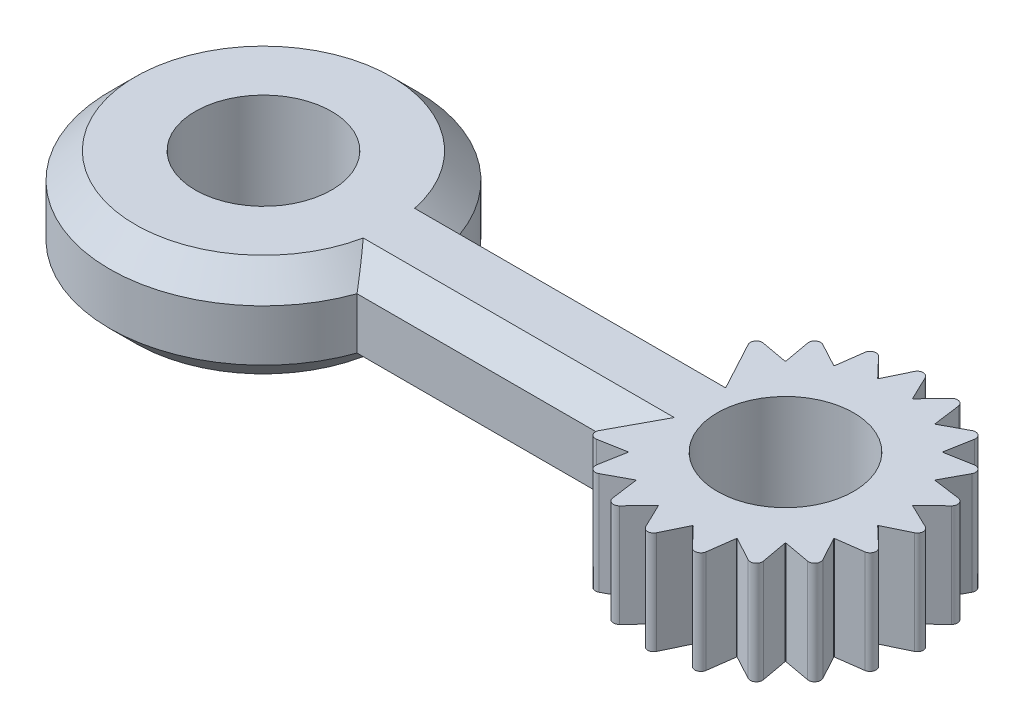
SolidWorks part; units mm, degrees
ref_plane "Front Plane" through (0, 0, 0) normal (0, 0, 1) x (1, 0, 0)
ref_plane "Top Plane" through (0, 0, 0) normal (0, 1, 0) x (1, 0, 0)
ref_plane "Right Plane" through (0, 0, 0) normal (1, 0, 0) x (0, 0, -1)
sketch "Sketch1" plane through (0, 0, 0) normal (0, 1, 0) x (1, 0, 0)
  line L0 (-21.5, 0) -> (-6.5, 0) construction
  line L1 (-22.0159, 3) -> (-5.7663, 3)
  line L2 (-22.0159, -3) -> (-5.7663, -3)
  line L3 (0, 6.5) -> (0, 8.5) construction
  line L4 (0, 8.5) -> (1, 6.4226)
  line L5 (0, 8.5) -> (-1, 6.4226)
  line L6 (2.6266, 8.084) -> (2.9358, 5.7993)
  line L7 (2.6266, 8.084) -> (1.0336, 6.4173)
  line L8 (4.9962, 6.8766) -> (4.5841, 4.6082)
  line L9 (4.9962, 6.8766) -> (2.9661, 5.7838)
  line L10 (6.8766, 4.9962) -> (5.7838, 2.9661)
  line L11 (6.8766, 4.9962) -> (4.6082, 4.5841)
  line L12 (8.084, 2.6266) -> (6.4173, 1.0336)
  line L13 (8.084, 2.6266) -> (5.7993, 2.9358)
  line L14 (8.5, 0) -> (6.4226, -1)
  line L15 (8.5, 0) -> (6.4226, 1)
  line L16 (8.084, -2.6266) -> (5.7993, -2.9358)
  line L17 (8.084, -2.6266) -> (6.4173, -1.0336)
  line L18 (6.8766, -4.9962) -> (4.6082, -4.5841)
  line L19 (6.8766, -4.9962) -> (5.7838, -2.9661)
  line L20 (4.9962, -6.8766) -> (2.9661, -5.7838)
  line L21 (4.9962, -6.8766) -> (4.5841, -4.6082)
  line L22 (2.6266, -8.084) -> (1.0336, -6.4173)
  line L23 (2.6266, -8.084) -> (2.9358, -5.7993)
  line L24 (0, -8.5) -> (-1, -6.4226)
  line L25 (0, -8.5) -> (1, -6.4226)
  line L26 (-2.6266, -8.084) -> (-2.9358, -5.7993)
  line L27 (-2.6266, -8.084) -> (-1.0336, -6.4173)
  line L28 (-4.9962, -6.8766) -> (-4.5841, -4.6082)
  line L29 (-4.9962, -6.8766) -> (-2.9661, -5.7838)
  line L30 (-6.8766, -4.9962) -> (-5.7838, -2.9661)
  line L31 (-6.8766, -4.9962) -> (-4.6082, -4.5841)
  line L32 (-5.802, 3) -> (-5.7838, 2.9661)
  line L39 (-6.8766, 4.9962) -> (-4.6082, 4.5841)
  line L40 (-6.8766, 4.9962) -> (-5.7838, 2.9661)
  line L41 (-4.9962, 6.8766) -> (-2.9661, 5.7838)
  line L42 (-8.084, -2.6266) -> (-6.4173, -1.0336) [skipped]
  line L43 (-8.084, -2.6266) -> (-5.7993, -2.9358) [skipped]
  line L44 (-6.8766, -4.9962) -> (-5.7838, -2.9661) [skipped]
  line L45 (-6.8766, -4.9962) -> (-4.6082, -4.5841) [skipped]
  line L46 (-8.5, 0) -> (-14.7322, 3) [skipped]
  line L47 (-8.5, 0) -> (-6.4226, 1) [skipped]
  line L48 (-8.084, 2.6266) -> (-6.4173, 1.0336) [skipped]
  line L49 (-8.084, 2.6266) -> (-5.7993, 2.9358) [skipped]
  line L50 (-6.8766, 4.9962) -> (-4.6082, 4.5841) [skipped]
  line L51 (-4.9962, 6.8766) -> (-4.5841, 4.6082) [skipped]
  line L52 (-4.9962, 6.8766) -> (-2.9661, 5.7838) [skipped]
  line L53 (-2.6266, 8.084) -> (-2.9358, 5.7993) [skipped]
  line L54 (-2.6266, 8.084) -> (-1.0336, 6.4173) [skipped]
  line L55 (2.6266, 8.084) -> (1.0336, 6.4173) [skipped]
  line L56 (2.6266, 8.084) -> (2.9358, 5.7993) [skipped]
  line L57 (4.9962, 6.8766) -> (2.9661, 5.7838) [skipped]
  line L58 (4.9962, 6.8766) -> (4.5841, 4.6082) [skipped]
  line L59 (6.8766, 4.9962) -> (4.6082, 4.5841) [skipped]
  line L60 (6.8766, 4.9962) -> (5.7838, 2.9661) [skipped]
  line L61 (8.084, 2.6266) -> (5.7993, 2.9358) [skipped]
  line L62 (8.084, 2.6266) -> (6.4173, 1.0336) [skipped]
  line L63 (8.5, 0) -> (6.4226, 1) [skipped]
  line L64 (8.5, 0) -> (6.4226, -1) [skipped]
  line L65 (8.084, -2.6266) -> (6.4173, -1.0336) [skipped]
  line L66 (8.084, -2.6266) -> (5.7993, -2.9358) [skipped]
  line L67 (6.8766, -4.9962) -> (5.7838, -2.9661) [skipped]
  line L68 (6.8766, -4.9962) -> (4.6082, -4.5841) [skipped]
  line L69 (4.9962, -6.8766) -> (4.5841, -4.6082) [skipped]
  line L70 (4.9962, -6.8766) -> (2.9661, -5.7838) [skipped]
  line L71 (2.6266, -8.084) -> (2.9358, -5.7993) [skipped]
  line L72 (2.6266, -8.084) -> (1.0336, -6.4173) [skipped]
  line L73 (0, -8.5) -> (1, -6.4226) [skipped]
  line L74 (0, -8.5) -> (-1, -6.4226) [skipped]
  line L75 (-2.6266, -8.084) -> (-1.0336, -6.4173) [skipped]
  line L76 (-2.6266, -8.084) -> (-2.9358, -5.7993) [skipped]
  line L77 (-4.9962, -6.8766) -> (-2.9661, -5.7838) [skipped]
  line L78 (-4.5841, -4.6082) -> (-4.4474, -3.8555) [skipped]
  line L79 (-4.9962, 6.8766) -> (-4.5841, 4.6082)
  line L80 (-2.6266, 8.084) -> (-1.0336, 6.4173)
  line L81 (-2.6266, 8.084) -> (-2.9358, 5.7993)
  line L82 (-8.5, 0) -> (-6.4226, -1) [skipped]
  line L83 (-8.5, 0) -> (-6.4226, 1) [skipped]
  line L84 (-8.084, 2.6266) -> (-6.4173, 1.0336) [skipped]
  line L85 (-8.084, 2.6266) -> (-5.7993, 2.9358) [skipped]
  line L86 (-8.084, -2.6266) -> (-6.4173, -1.0336) [skipped]
  line L87 (-8.084, -2.6266) -> (-5.7993, -2.9358) [skipped]
  arc A0 (-5.7663, -3) -> (-5.7663, 3) centre (0, 0) ccw
  circle A1 centre (0, 0) radius 3.98
  circle A2 centre (-30.48, 0) radius 3.98
  arc A3 (-22.0159, 3) -> (-22.0159, -3) centre (-30.48, 0) ccw
  point P66 (0, 0)
  point P152 (0, 0)
  dimension "D1" = 13
  dimension "D2" = 7.96
  dimension "D7" = 2
  dimension "D10" = 5
  dimension "D3" = 15
  dimension "D4" = 3
  dimension "D8" = 2
  dimension "D9" = 20
extrude "Boss-Extrude1" add sketch "Sketch1" along normal blind 6
fillet "Fillet1" radius 0.35 17 edges at (-6.8766, 3, 4.9962) (-4.9962, 3, 6.8766) (-2.6266, 3, 8.084) (0, 3, 8.5) (2.6266, 3, 8.084) (4.9962, 3, 6.8766) (6.8766, 3, 4.9962) (8.084, 3, 2.6266) (8.5, 3, 0) (8.084, 3, -2.6266) (6.8766, 3, -4.9962) (4.9962, 3, -6.8766) (2.6266, 3, -8.084) (0, 3, -8.5) (-2.6266, 3, -8.084) (-4.9962, 3, -6.8766) (-6.8766, 3, -4.9962)
chamfer "Chamfer1" distance 1.5 angle 45 6 edges at (-13.909, 0, 3) (-13.909, 6, 3) (-13.909, 0, -3) (-13.909, 6, -3) (-39.46, 0, 0) (-39.46, 6, 0)
